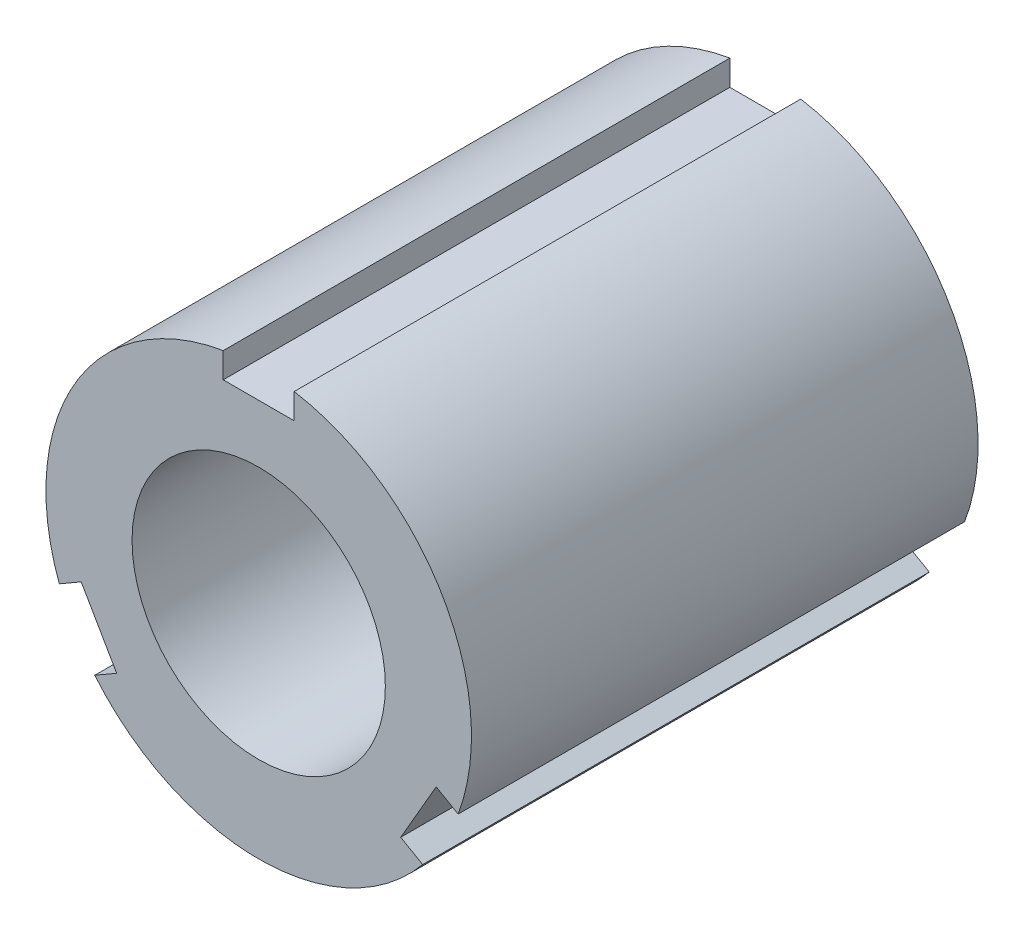
SolidWorks part; units mm, degrees
ref_plane "Спереди" through (0, 0, 0) normal (0, 0, 1) x (1, 0, 0)
ref_plane "Сверху" through (0, 0, 0) normal (0, 1, 0) x (1, 0, 0)
ref_plane "Справа" through (0, 0, 0) normal (1, 0, 0) x (0, 0, -1)
sketch "Эскиз1" plane through (0, 0, 0) normal (0, 0, 1) x (1, 0, 0)
  line L2 (-3.5, 20.7063) -> (-3.5, 18.2063)
  line L3 (-3.5, 18.2063) -> (3.5, 18.2063)
  line L4 (3.5, 20.7063) -> (3.5, 18.2063)
  line L6 (-3.5, 20.7063) -> (-3.5, 22.7063)
  line L7 (-3.5, 22.7063) -> (3.5, 22.7063)
  line L8 (3.5, 20.7063) -> (3.5, 22.7063)
  line L50 (19.6822, -7.3221) -> (17.5171, -6.0721)
  line L51 (17.5171, -6.0721) -> (14.0171, -12.1342)
  line L52 (16.1822, -13.3842) -> (14.0171, -12.1342)
  line L53 (19.6822, -7.3221) -> (21.4142, -8.3221)
  line L54 (21.4142, -8.3221) -> (17.9142, -14.3842)
  line L55 (16.1822, -13.3842) -> (17.9142, -14.3842)
  line L56 (-16.1822, -13.3842) -> (-14.0171, -12.1342)
  line L57 (-14.0171, -12.1342) -> (-17.5171, -6.0721)
  line L58 (-19.6822, -7.3221) -> (-17.5171, -6.0721)
  line L59 (-16.1822, -13.3842) -> (-17.9142, -14.3842)
  line L60 (-17.9142, -14.3842) -> (-21.4142, -8.3221)
  line L61 (-19.6822, -7.3221) -> (-21.4142, -8.3221)
  circle A0 centre (0, 0) radius 21
  circle A1 centre (0, 0) radius 12.5
  point P24 (0, 0)
  point P54 (0, 0)
  dimension "D1" = 42
  dimension "D2" = 25
  dimension "D3" = 7
  dimension "D4" = 2.5
  dimension "D5" = 2
  dimension "D6" = 3
extrude "Бобышка-Вытянуть1" add sketch "Эскиз1" along normal blind 50
